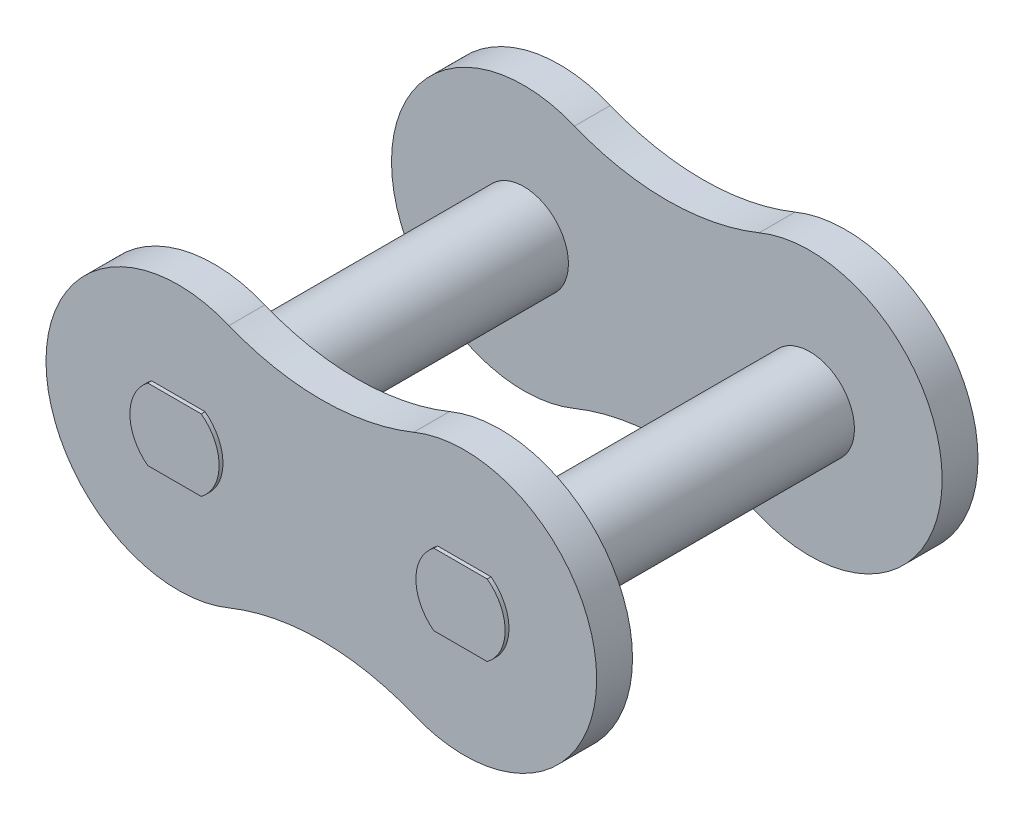
SolidWorks part; units mm, degrees
material "AISI 1020"
ref_plane "Front Plane" through (0, 0, 0) normal (0, 0, 1) x (1, 0, 0)
ref_plane "Top Plane" through (0, 0, 0) normal (0, 1, 0) x (1, 0, 0)
ref_plane "Right Plane" through (0, 0, 0) normal (1, 0, 0) x (0, 0, -1)
sketch "Sketch1" plane through (0, 0, 0) normal (0, 0, 1) x (1, 0, 0)
  line L0 (0, 0) -> (-9.525, 0) construction
  line L1 (0, 0) -> (9.525, 0) construction
  line L2 (-9.525, 8.8138) -> (9.525, 8.8138)
  line L3 (9.525, 8.8138) -> (0.7112, 0)
  line L4 (0.7112, 0) -> (-0.7112, 0)
  line L5 (-0.7112, 0) -> (-9.525, 8.8138)
  line L6 (-5.1181, 4.4069) -> (-3.2927, 6.2323)
  line L7 (-3.2927, 6.2323) -> (3.2927, 6.2323)
  line L8 (3.2927, 6.2323) -> (5.1181, 4.4069)
  line L9 (0, 6.2323) -> (0, 8.8138)
  circle A0 centre (-9.525, 0) radius 2.9718
  circle A1 centre (9.525, 0) radius 2.9718
  circle A2 centre (-9.525, 0) radius 8.8138
  circle A3 centre (9.525, 0) radius 8.8138
  arc A4 (-9.525, 8.8138) -> (-3.2927, 6.2323) centre (-9.525, 0) cw
  arc A5 (3.2927, 6.2323) -> (9.525, 8.8138) centre (9.525, 0) cw
  arc A6 (6.1521, 8.1429) -> (-6.1521, 8.1429) centre (0, 23.3329) cw
  arc A7 (6.1521, -8.1429) -> (-6.1521, -8.1429) centre (0, -23.3329) ccw
  dimension "D3" = 5.9436
  dimension "D4" = 5.9436
  dimension "D5" = 17.6276
  dimension "D6" = 17.6276
  dimension "D1" = 9.525
  dimension "D2" = 9.525
extrude "Boss-Extrude1" add sketch "Sketch1" along normal blind 2.3876 contours L5 A2 A0 | L5 A2 L6 | A3 L7 A2 L4 | A7 A3 L4 A2 | L3 A3 A1 | L8 A3 L3 | L3 A3 A5 L8 | A5 A6 L9 L7 | L9 A6 A2 L7 | L6 A2 A4 L5
sketch "Sketch2" plane through (0, 0, 0) normal (0, 0, -1) x (-1, 0, 0)
  circle A0 centre (9.525, 0) radius 2.9718
  circle A1 centre (-9.525, 0) radius 2.9718
extrude "Boss-Extrude2" add sketch "Sketch2" against normal blind 25.4
sketch "Sketch3" plane through (0, 0, 25.4) normal (0, 0, 1) x (1, 0, 0)
  arc A4 (6.1521, -8.1429) -> (6.1521, 8.1429) centre (9.525, 0) ccw
  arc A5 (-6.1521, 8.1429) -> (6.1521, 8.1429) centre (0, 23.3329) ccw
  arc A6 (-6.1521, 8.1429) -> (-6.1521, -8.1429) centre (-9.525, 0) ccw
  arc A7 (6.1521, -8.1429) -> (-6.1521, -8.1429) centre (0, -23.3329) ccw
  arc A8 (6.1521, -8.1429) -> (6.1521, 8.1429) centre (9.525, 0) ccw
  arc A9 (-6.1521, 8.1429) -> (6.1521, 8.1429) centre (0, 23.3329) ccw
  arc A10 (-6.1521, 8.1429) -> (-6.1521, -8.1429) centre (-9.525, 0) ccw
  arc A11 (6.1521, -8.1429) -> (-6.1521, -8.1429) centre (0, -23.3329) ccw
  dimension "D1" = 0
extrude "Boss-Extrude3" add sketch "Sketch3" against normal blind 2.3876
sketch "Sketch4" plane through (0, 0, 25.4) normal (0, 0, 1) x (1, 0, 0)
  line L0 (0, 0) -> (0, 3.1863) construction
  line L1 (-5.715, -2.3812) -> (-13.335, -2.3813)
  line L2 (-5.715, -2.3812) -> (-5.715, 2.3813)
  line L3 (-5.715, 2.3813) -> (-13.335, 2.3812)
  line L4 (-13.335, -2.3813) -> (-13.335, 2.3812)
  line L5 (-5.715, -2.3812) -> (-13.335, 2.3812) construction
  line L6 (-5.715, 2.3813) -> (-13.335, -2.3813) construction
  line L7 (5.715, -2.3812) -> (13.335, -2.3813)
  line L8 (5.715, -2.3812) -> (5.715, 2.3813)
  line L9 (5.715, 2.3813) -> (13.335, 2.3812)
  line L10 (13.335, -2.3813) -> (13.335, 2.3812)
  circle A0 centre (-9.525, 0) radius 2.9718
  circle A1 centre (9.525, 0) radius 2.9718
  dimension "D1" = 5.9436
  dimension "D2" = 5.9436
  dimension "D3" = 4.7625
  dimension "D4" = 7.62
extrude "Boss-Extrude4" add sketch "Sketch4" along normal blind 0.254 contours L3 A0 L1 | L9 A1 L7
ref_plane "Plane1" through (0, 0, 12.7) normal (0, 0, 1) x (1, 0, 0)
mirror "Mirror1" about plane through (0, 0, 12.7) normal (0, 0, 1) of "Boss-Extrude4"
